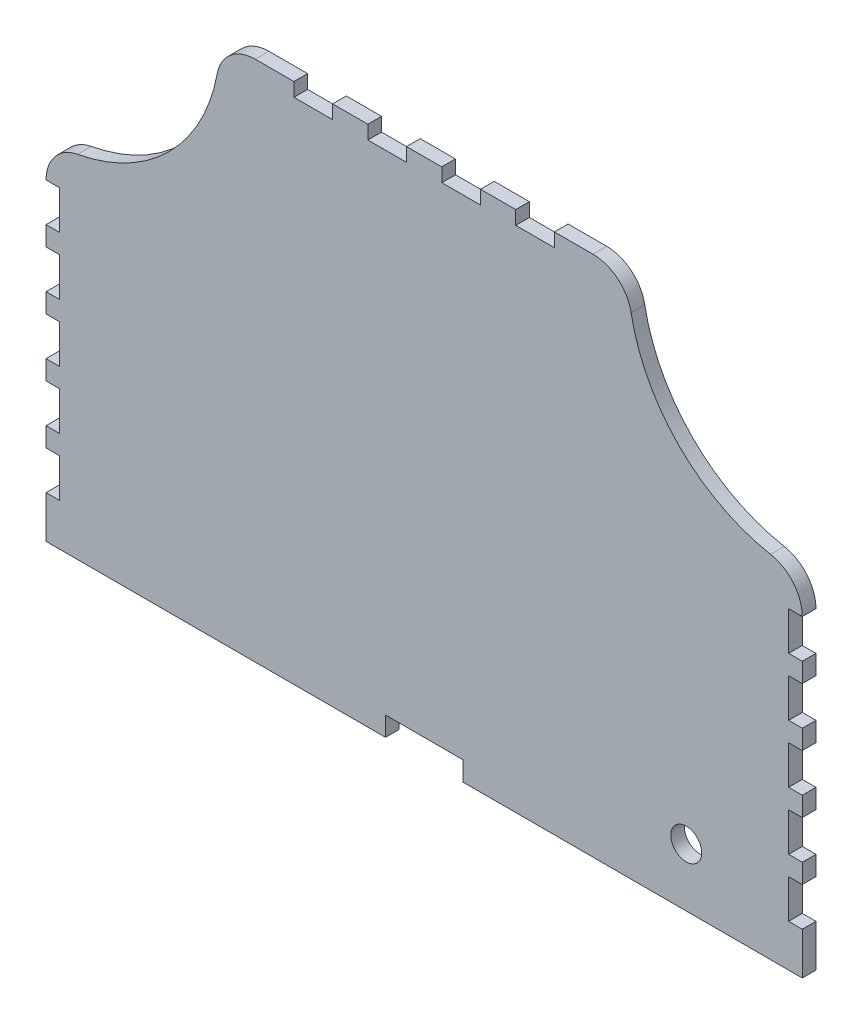
SolidWorks part; units mm, degrees
ref_plane "Front Plane" through (0, 0, 0) normal (0, 0, 1) x (1, 0, 0)
ref_plane "Top Plane" through (0, 0, 0) normal (0, 1, 0) x (1, 0, 0)
ref_plane "Right Plane" through (0, 0, 0) normal (1, 0, 0) x (0, 0, -1)
sketch "Sketch1" plane through (0, 0, 0) normal (0, 0, 1) x (1, 0, 0)
  line L1 (0, 0) -> (248.285, 0)
  line L2 (0, 0) -> (0, 171.45)
  line L3 (0, 171.45) -> (248.285, 171.45)
  line L4 (248.285, 0) -> (248.285, 171.45)
  circle A0 centre (0, 171.45) radius 57.15
  circle A1 centre (248.285, 171.45) radius 57.15
  dimension "D3" = 114.3
  dimension "D1" = 171.45
  dimension "D2" = 248.285
extrude "Boss-Extrude1" add sketch "Sketch1" along normal blind 4.4958 contours A1 L3 A0 L2 L1 L4
fillet "Fillet1" radius 12.7 4 edges at (0, 114.3, 2.2479) (248.285, 114.3, 2.2479) (191.135, 171.45, 2.2479) (57.15, 171.45, 2.2479)
sketch "Sketch2" plane through (0, 0, 4.4958) normal (0, 0, 1) x (1, 0, 0)
  line L0 (0, 83.7142) -> (4.4958, 83.7142)
  line L1 (0, 102.7642) -> (4.4958, 102.7642)
  line L2 (0, 102.7642) -> (0, 90.0642)
  line L3 (0, 90.0642) -> (4.4958, 90.0642)
  line L4 (4.4958, 102.7642) -> (4.4958, 90.0642)
  line L5 (4.4958, 83.7142) -> (4.4958, 71.0142)
  line L6 (0, 71.0142) -> (4.4958, 71.0142)
  line L7 (0, 64.6642) -> (4.4958, 64.6642)
  line L8 (4.4958, 64.6642) -> (4.4958, 51.9642)
  line L9 (0, 51.9642) -> (4.4958, 51.9642)
  line L10 (0, 45.6142) -> (4.4958, 45.6142)
  line L11 (4.4958, 45.6142) -> (4.4958, 32.9142)
  line L12 (0, 32.9142) -> (4.4958, 32.9142)
  line L13 (0, 26.5642) -> (4.4958, 26.5642)
  line L14 (4.4958, 26.5642) -> (4.4958, 13.8642)
  line L15 (0, 13.8642) -> (4.4958, 13.8642)
  line L16 (124.1425, 171.45) -> (124.1425, 0) construction
  line L17 (68.6858, 171.45) -> (179.5992, 171.45) construction
  line L18 (0, 0) -> (248.285, 0) construction
  line L19 (248.285, 13.8642) -> (243.7892, 13.8642)
  line L20 (243.7892, 26.5642) -> (243.7892, 13.8642)
  line L21 (248.285, 26.5642) -> (243.7892, 26.5642)
  line L22 (248.285, 32.9142) -> (243.7892, 32.9142)
  line L23 (243.7892, 45.6142) -> (243.7892, 32.9142)
  line L24 (248.285, 45.6142) -> (243.7892, 45.6142)
  line L25 (248.285, 51.9642) -> (243.7892, 51.9642)
  line L26 (243.7892, 64.6642) -> (243.7892, 51.9642)
  line L27 (248.285, 64.6642) -> (243.7892, 64.6642)
  line L28 (243.7892, 83.7142) -> (243.7892, 71.0142)
  line L29 (248.285, 83.7142) -> (243.7892, 83.7142)
  line L30 (248.285, 71.0142) -> (243.7892, 71.0142)
  line L31 (248.285, 90.0642) -> (243.7892, 90.0642)
  line L32 (243.7892, 102.7642) -> (243.7892, 90.0642)
  line L33 (248.285, 102.7642) -> (243.7892, 102.7642)
  line L34 (248.285, 102.7642) -> (248.285, 90.0642)
  line M20 (0, 102.7642) -> (0, 0)
  line M22 (248.285, 0) -> (248.285, 102.7642)
  dimension "D2" = 4.4958
  dimension "D3" = 12.7
  dimension "D1" = 5
extrude "Cut-Extrude1" cut sketch "Sketch2" against normal through all contours L33 L32 L31 M22 | L30 L29 L28 M22 | L24 L23 L22 M22 | L27 L26 L25 M22 | L21 L20 L19 M22 | L4 L1 L3 M20 | L6 L5 L0 M20 | L9 L8 L7 M20 | L12 L11 L10 M20 | L15 L14 L13 M20
sketch "Sketch3" plane through (0, 0, 4.4958) normal (0, 0, 1) x (1, 0, 0)
  line L0 (105.6569, 171.45) -> (105.6569, 166.9542)
  line L1 (81.3858, 171.45) -> (94.0858, 171.45)
  line L2 (81.3858, 171.45) -> (81.3858, 166.9542)
  line L3 (81.3858, 166.9542) -> (94.0858, 166.9542)
  line L4 (94.0858, 171.45) -> (94.0858, 166.9542)
  line L5 (105.6569, 171.45) -> (118.3569, 171.45)
  line L6 (118.3569, 171.45) -> (118.3569, 166.9542)
  line L7 (105.6569, 166.9542) -> (118.3569, 166.9542)
  line L8 (129.9281, 171.45) -> (129.9281, 166.9542)
  line L9 (129.9281, 171.45) -> (142.6281, 171.45)
  line L10 (142.6281, 171.45) -> (142.6281, 166.9542)
  line L11 (129.9281, 166.9542) -> (142.6281, 166.9542)
  line L12 (154.1992, 171.45) -> (154.1992, 166.9542)
  line L13 (154.1992, 171.45) -> (166.8992, 171.45)
  line L14 (166.8992, 171.45) -> (166.8992, 166.9542)
  line L15 (154.1992, 166.9542) -> (166.8992, 166.9542)
  line L16 (68.6858, 171.45) -> (179.5992, 171.45) construction
  dimension "D1" = 12.7
  dimension "D2" = 12.7
  dimension "D3" = 4.4958
  dimension "D5" = 12.7
  dimension "D4" = 4
extrude "Cut-Extrude2" cut sketch "Sketch3" against normal through all
sketch "Sketch4" plane through (0, 0, 4.4958) normal (0, 0, 1) x (1, 0, 0)
  line L0 (0, 0) -> (248.285, 0) construction
  line L1 (248.285, 0) -> (248.285, 13.8642) construction
  circle A0 centre (210.185, 19.05) radius 5.08
  dimension "D1" = 10.16
  dimension "D2" = 19.05
  dimension "D3" = 38.1
extrude "Cut-Extrude3" cut sketch "Sketch4" against normal through all
sketch "Sketch5" plane through (0, 0, 4.4958) normal (0, 0, 1) x (1, 0, 0)
  line L0 (0, 0) -> (248.285, 0) construction
  line L1 (111.4425, 0) -> (136.8425, 0)
  line L2 (111.4425, 0) -> (111.4425, 6.35)
  line L3 (111.4425, 6.35) -> (136.8425, 6.35)
  line L4 (136.8425, 0) -> (136.8425, 6.35)
  point P6 (124.1425, 0)
  point P7 (124.1425, 0)
  dimension "D1" = 25.4
  dimension "D2" = 6.35
extrude "Cut-Extrude4" cut sketch "Sketch5" against normal through all
